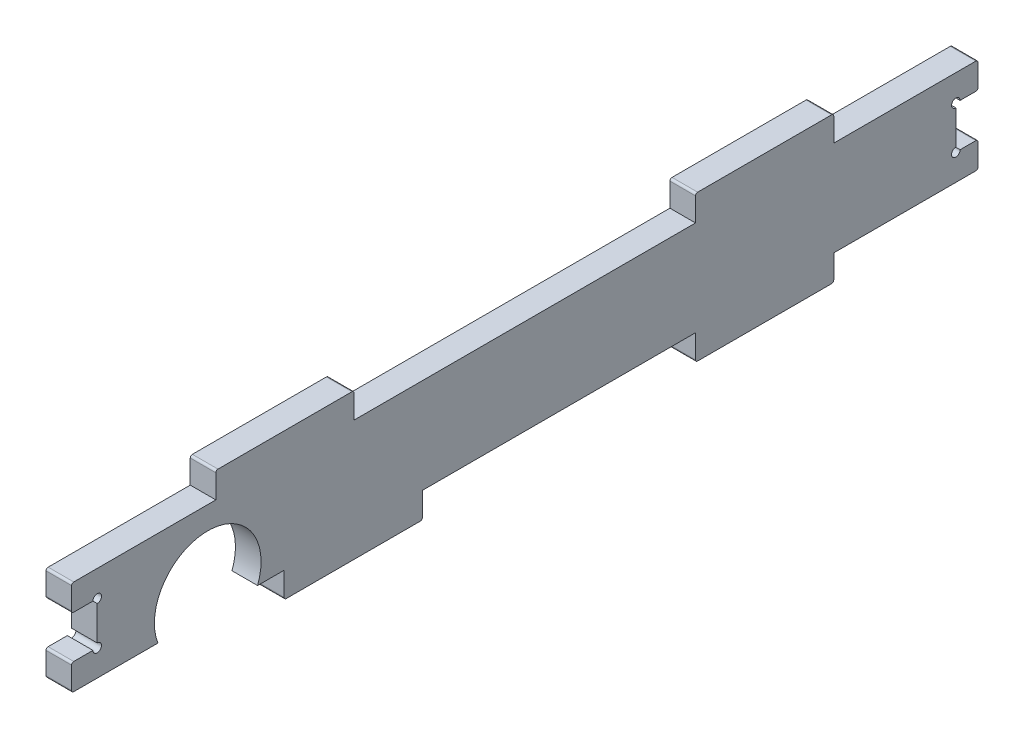
SolidWorks part; units mm, degrees
material "Acrylic (Medium-high impact)"
ref_plane "Front Plane" through (0, 0, 0) normal (0, 0, 1) x (1, 0, 0)
ref_plane "Top Plane" through (0, 0, 0) normal (0, 1, 0) x (1, 0, 0)
ref_plane "Right Plane" through (0, 0, 0) normal (1, 0, 0) x (0, 0, -1)
sketch "Sketch3" plane through (0, 0, 0) normal (1, 0, 0) x (0, 0, -1)
  line L0 (73.4863, 19.2019) -> (89.1863, 19.2019)
  line L1 (25.2863, 2.0644) -> (40.9863, 2.0644)
  line L2 (0.1363, 5.3144) -> (0.1363, 7.8832)
  line L3 (17.2863, 19.2019) -> (32.9863, 19.2019)
  line L4 (106.3363, 5.3144) -> (106.3363, 7.8832)
  line L5 (0.1363, 13.3832) -> (0.1363, 15.9519)
  line L6 (17.0363, 18.9519) -> (17.0363, 16.2019)
  line L7 (33.2363, 16.2019) -> (73.2363, 16.2019)
  line L8 (33.2363, 18.9519) -> (33.2363, 16.2019)
  line L9 (0.3863, 13.1332) -> (2.6363, 13.1332)
  line L10 (73.2363, 18.9519) -> (73.2363, 16.2019)
  line L11 (89.4363, 16.2019) -> (106.0863, 16.2019)
  line L12 (89.4363, 18.9519) -> (89.4363, 16.2019)
  line L13 (0.3863, 16.2019) -> (17.0363, 16.2019)
  line L14 (106.3363, 13.3832) -> (106.3363, 15.9519)
  line L15 (0.3863, 5.0644) -> (10.2458, 5.0644)
  line L16 (0.3863, 8.1332) -> (2.6363, 8.1332)
  line L17 (73.4863, 2.0644) -> (89.1863, 2.0644)
  line L18 (3.1363, 12.6332) -> (3.1363, 8.6332)
  line L19 (25.0363, 5.0644) -> (25.0363, 2.3144)
  line L20 (106.0863, 13.1332) -> (104.2363, 13.1332)
  line L21 (41.2363, 5.0644) -> (41.2363, 2.3144)
  line L22 (89.4363, 5.0644) -> (106.0863, 5.0644)
  line L23 (73.2363, 5.0644) -> (73.2363, 2.3144)
  line L24 (21.9269, 5.0644) -> (25.0363, 5.0644)
  line L25 (89.4363, 5.0644) -> (89.4363, 2.3144)
  line L26 (41.2363, 5.0644) -> (73.2363, 5.0644)
  line L27 (106.0863, 8.1332) -> (104.2363, 8.1332)
  line L28 (103.7363, 12.6332) -> (103.7363, 8.6332)
  arc A0 (3.1363, 12.6332) -> (2.6363, 13.1332) centre (3.1363, 13.1332) ccw
  arc A1 (2.6363, 8.1332) -> (3.1363, 8.6332) centre (3.1363, 8.1332) ccw
  arc A2 (103.7363, 8.6332) -> (104.2363, 8.1332) centre (103.7363, 8.1332) ccw
  arc A3 (104.2363, 13.1332) -> (103.7363, 12.6332) centre (103.7363, 13.1332) ccw
  arc A4 (106.0863, 5.0644) -> (106.3363, 5.3144) centre (106.0863, 5.3144) ccw
  arc A5 (106.3363, 7.8832) -> (106.0863, 8.1332) centre (106.0863, 7.8832) ccw
  arc A6 (106.0863, 13.1332) -> (106.3363, 13.3832) centre (106.0863, 13.3832) ccw
  arc A7 (106.3363, 15.9519) -> (106.0863, 16.2019) centre (106.0863, 15.9519) ccw
  arc A8 (89.4363, 18.9519) -> (89.1863, 19.2019) centre (89.1863, 18.9519) ccw
  arc A9 (73.4863, 19.2019) -> (73.2363, 18.9519) centre (73.4863, 18.9519) ccw
  arc A10 (33.2363, 18.9519) -> (32.9863, 19.2019) centre (32.9863, 18.9519) ccw
  arc A11 (17.2863, 19.2019) -> (17.0363, 18.9519) centre (17.2863, 18.9519) ccw
  arc A12 (0.3863, 16.2019) -> (0.1363, 15.9519) centre (0.3863, 15.9519) ccw
  arc A13 (0.1363, 13.3832) -> (0.3863, 13.1332) centre (0.3863, 13.3832) ccw
  arc A14 (0.3863, 8.1332) -> (0.1363, 7.8832) centre (0.3863, 7.8832) ccw
  arc A15 (0.1363, 5.3144) -> (0.3863, 5.0644) centre (0.3863, 5.3144) ccw
  arc A16 (25.0363, 2.3144) -> (25.2863, 2.0644) centre (25.2863, 2.3144) ccw
  arc A17 (40.9863, 2.0644) -> (41.2363, 2.3144) centre (40.9863, 2.3144) ccw
  arc A18 (73.2363, 2.3144) -> (73.4863, 2.0644) centre (73.4863, 2.3144) ccw
  arc A19 (89.1863, 2.0644) -> (89.4363, 2.3144) centre (89.1863, 2.3144) ccw
  arc A20 (21.9269, 5.0644) -> (10.2458, 5.0644) centre (16.0863, 7.2894) ccw
  dimension "D19" = 1
  dimension "D25" = 0.5
  dimension "D28" = 0.5
  dimension "D7" = 0.25
  dimension "D33" = 0.5
  dimension "D64" = 0.25
  dimension "D65" = 0.25
  dimension "D66" = 0.25
  dimension "D67" = 0.25
  dimension "D68" = 0.25
  dimension "D69" = 0.25
  dimension "D70" = 0.25
  dimension "D71" = 0.25
  dimension "D72" = 0.25
  dimension "D73" = 0.25
  dimension "D74" = 0.25
  dimension "D75" = 0.25
  dimension "D76" = 0.25
  dimension "D78" = 12.5
  dimension "D3" = 16.9
  dimension "D4" = 106.2
  dimension "D8" = 16.9
  dimension "D9" = 24.9
  dimension "D10" = 3
  dimension "D11" = 17.1375
  dimension "D12" = 5
  dimension "D13" = 3.0688
  dimension "D14" = 3
  dimension "D15" = 16.2
  dimension "D16" = 16.2
  dimension "D17" = 3.0688
  dimension "D18" = 5
  dimension "D20" = 5
  dimension "D21" = 0.5
  dimension "D22" = 0.5
  dimension "D23" = 0.5
  dimension "D24" = 0.5
  dimension "D26" = 0.5
  dimension "D27" = 0.5
  dimension "D29" = 0.25
  dimension "D30" = 0.25
  dimension "D31" = 0.25
  dimension "D32" = 0.25
  dimension "D34" = 0.25
  dimension "D35" = 0.25
  dimension "D36" = 0.25
  dimension "D37" = 0.25
  dimension "D38" = 0.25
  dimension "D39" = 0.25
  dimension "D40" = 0.25
  dimension "D41" = 0.25
  dimension "D42" = 0.25
  dimension "D43" = 0.25
  dimension "D44" = 0.25
  dimension "D45" = 0.25
  dimension "D46" = 0.25
  dimension "D47" = 0.25
  dimension "D48" = 0.25
  dimension "D49" = 0.25
  dimension "D50" = 0.25
  dimension "D51" = 0.25
  dimension "D52" = 0.25
  dimension "D53" = 0.25
  dimension "D54" = 0.25
  dimension "D55" = 0.25
  dimension "D56" = 0.25
  dimension "D57" = 0.25
  dimension "D58" = 0.25
  dimension "D59" = 0.25
  dimension "D60" = 0.25
  dimension "D61" = 0.25
  dimension "D62" = 16.2
  dimension "D63" = 16.2
  dimension "D77" = 16.9
  dimension "D79" = 12.95
  dimension "D80" = 2.225
extrude "Boss-Extrude1" add sketch "Sketch3" along normal blind 3
